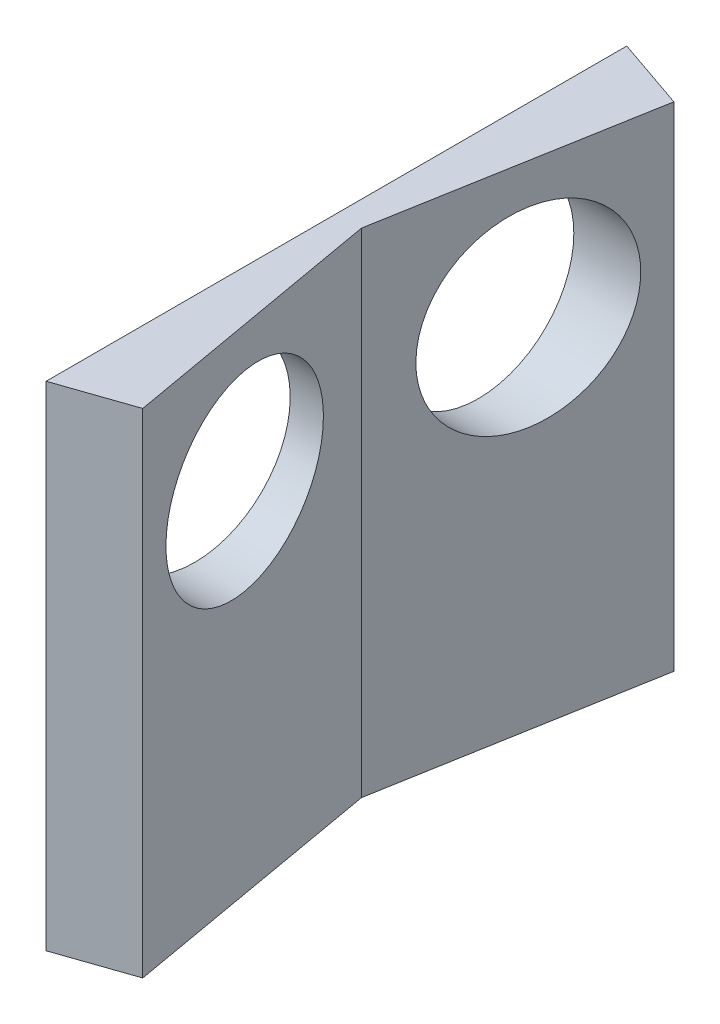
SolidWorks part; units mm, degrees
ref_plane "Front Plane" through (0, 0, 0) normal (0, 0, 1) x (1, 0, 0)
ref_plane "Top Plane" through (0, 0, 0) normal (0, 1, 0) x (1, 0, 0)
ref_plane "Right Plane" through (0, 0, 0) normal (1, 0, 0) x (0, 0, -1)
sketch "Sketch3" plane through (0, 0, 0) normal (0, 1, 0) x (1, 0, 0)
  line L0 (0, -23.545) -> (5.8284, -21.5367)
  line L1 (0, 23.545) -> (0, -23.545)
  line L2 (5.8284, -21.5367) -> (2.0309, 0)
  line L3 (2.0309, 0) -> (5.8284, 21.5367)
  line L4 (5.8284, 21.5367) -> (0, 23.545)
  point P5 (0, 0)
  dimension "D1" = 70.988
  dimension "D2" = 70.988
  dimension "D3" = 160
  dimension "D4" = 6.1647
  dimension "D5" = 6.1647
  dimension "D6" = 47.09
  dimension "D7" = 21.869
extrude "Boss-Extrude2" add sketch "Sketch3" along normal blind 40
sketch "Sketch4" plane through (0, 0, 0) normal (-1, 0, 0) x (0, 0, 1)
  line L0 (-23.545, 40) -> (23.545, 40) construction
  circle A0 centre (-11.5, 29) radius 7.75
  circle A1 centre (11.5, 29) radius 7.75
  dimension "D1" = 15.5
  dimension "D2" = 11
  dimension "D3" = 23
  dimension "D4" = 11.5
extrude "Cut-Extrude1" cut sketch "Sketch4" against normal up to body
